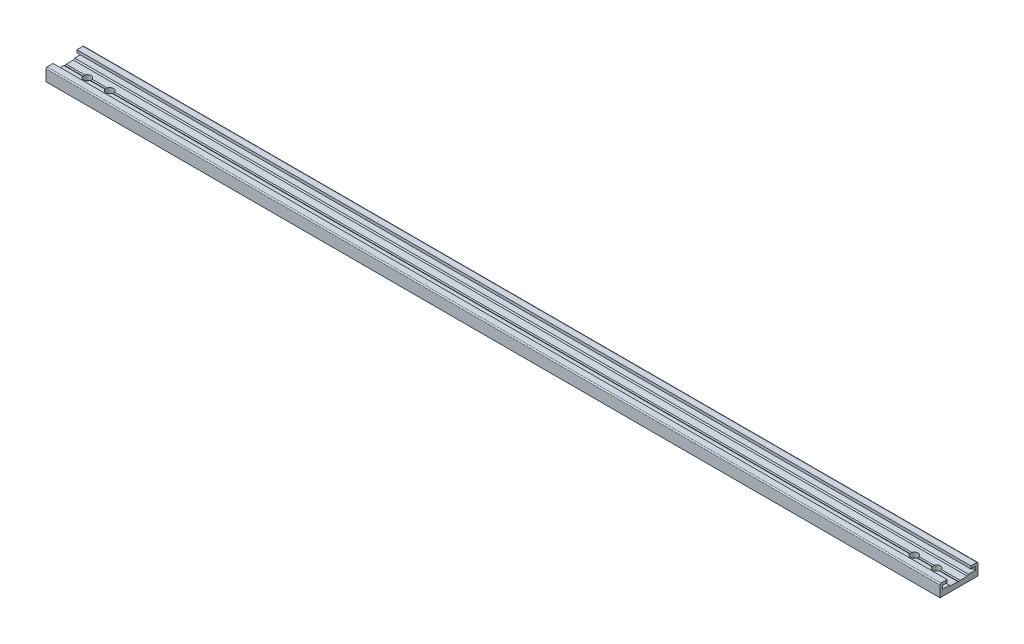
SolidWorks part; units mm, degrees
material "6061 Alloy"
ref_plane "Front" through (0, 0, 0) normal (0, 0, 1) x (1, 0, 0)
ref_plane "Top" through (0, 0, 0) normal (0, 1, 0) x (1, 0, 0)
ref_plane "Right" through (0, 0, 0) normal (1, 0, 0) x (0, 0, -1)
sketch "Sketch1" plane through (0, 0, 0) normal (1, 0, 0) x (0, 0, -1)
  line L0 (0, -2.75) -> (0, 2.75) construction
  line L1 (-0.5, -0.45) -> (0, -0.7387) construction
  line L2 (-3.75, -0.45) -> (-0.5, -0.45) construction
  line L3 (-4.25, 0.05) -> (-3.75, -0.45) construction
  line L4 (-7.3, 0.05) -> (-4.25, 0.05) construction
  line L5 (-7.3, 1.55) -> (-7.3, 0.05) construction
  line L6 (-5.3, 1.55) -> (-7.3, 1.55) construction
  line L7 (-5.3, 2.75) -> (-5.3, 1.55) construction
  line L8 (-8, 2.75) -> (-5.3, 2.75) construction
  line L9 (-8.5, -2.75) -> (-8.5, 2.25) construction
  line L39 (-8.5, -2.75) -> (8.5, -2.75) construction
  line L40 (8.5, -2.75) -> (8.5, 2.25) construction
  line L41 (8, 2.75) -> (5.3, 2.75) construction
  line L42 (5.3, 2.75) -> (5.3, 1.55) construction
  line L43 (5.3, 1.55) -> (7.3, 1.55) construction
  line L44 (7.3, 1.55) -> (7.3, 0.05) construction
  line L45 (7.3, 0.05) -> (4.25, 0.05) construction
  line L46 (4.25, 0.05) -> (3.75, -0.45) construction
  line L47 (3.75, -0.45) -> (0.5, -0.45) construction
  line L48 (0.5, -0.45) -> (0, -0.7387) construction
  arc A0 (8, 2.75) -> (8.5, 2.25) centre (8, 2.25) cw construction
  arc A1 (-8, 2.75) -> (-8.5, 2.25) centre (-8, 2.25) ccw construction
  point P1 (7.3, 0.8)
  point P26 (0, 0)
  point P32 (0, -1.75)
  dimension "D12" = 0.5
  dimension "D1" = 30
  dimension "D3" = 2.3
  dimension "Rail Height" = 5.5
  dimension "D4" = 2.0113
  dimension "D5" = 2.8
  dimension "D7" = 1.2
  dimension "D8" = 3.2
  dimension "D9" = 1.2
  dimension "D10" = 45
  dimension "D11" = 3.75
  dimension "Rail Width" = 17
  dimension "Mounting Hole Depth" = 1
sketch "Sketch2" plane through (0, 0, 0) normal (0, 0, 1) x (1, 0, 0)
  line L0 (1000, 0) -> (-1000, 0) construction
  point P0 (-960, 0)
  point P3 (-900, 0)
  point P4 (0, 0)
  point P6 (-884, 0)
  point P7 (988, 0)
  dimension "Rail Length" = 2000
  dimension "Mounting Hole Ctr to End" = 40
  dimension "Mounting Hole Ctr to Ctr" = 60
  dimension "D2" = 12
  dimension "D1" = 16
sketch "Sketch5" plane through (0, 0, 0) normal (1, 0, 0) x (0, 0, -1)
  line L0 (-8.5, -2.75) -> (8.5, -2.75) construction
  line L1 (8.5, -2.75) -> (8.5, 2.25) construction
  line L2 (8, 2.75) -> (5.3, 2.75) construction
  line L3 (5.3, 2.75) -> (5.3, 1.55) construction
  line L4 (5.3, 1.55) -> (7.3, 1.55) construction
  line L5 (7.3, 1.55) -> (7.3, 0.05) construction
  line L6 (7.3, 0.05) -> (4.25, 0.05) construction
  line L7 (4.25, 0.05) -> (3.75, -0.45) construction
  line L8 (3.75, -0.45) -> (0.5, -0.45) construction
  line L9 (0.5, -0.45) -> (0, -0.7387) construction
  line L10 (-0.5, -0.45) -> (0, -0.7387) construction
  line L11 (-3.75, -0.45) -> (-0.5, -0.45) construction
  line L12 (-4.25, 0.05) -> (-3.75, -0.45) construction
  line L13 (-7.3, 0.05) -> (-4.25, 0.05) construction
  line L14 (-7.3, 1.55) -> (-7.3, 0.05) construction
  line L15 (-5.3, 1.55) -> (-7.3, 1.55) construction
  line L16 (-5.3, 2.75) -> (-5.3, 1.55) construction
  line L17 (-8, 2.75) -> (-5.3, 2.75) construction
  line L18 (-8.5, -2.75) -> (-8.5, 2.25) construction
  line L19 (-8.5, -2.75) -> (8.5, -2.75)
  line L20 (8.5, -2.75) -> (8.5, 2.25)
  line L21 (8, 2.75) -> (5.3, 2.75)
  line L22 (5.3, 2.75) -> (5.3, 1.55)
  line L23 (5.3, 1.55) -> (7.3, 1.55)
  line L24 (7.3, 1.55) -> (7.3, 0.05)
  line L25 (7.3, 0.05) -> (4.25, 0.05)
  line L26 (4.25, 0.05) -> (3.75, -0.45)
  line L27 (3.75, -0.45) -> (0.5, -0.45)
  line L28 (0.5, -0.45) -> (0, -0.7387)
  line L29 (-0.5, -0.45) -> (0, -0.7387)
  line L30 (-3.75, -0.45) -> (-0.5, -0.45)
  line L31 (-4.25, 0.05) -> (-3.75, -0.45)
  line L32 (-7.3, 0.05) -> (-4.25, 0.05)
  line L33 (-7.3, 1.55) -> (-7.3, 0.05)
  line L34 (-5.3, 1.55) -> (-7.3, 1.55)
  line L35 (-5.3, 2.75) -> (-5.3, 1.55)
  line L36 (-8, 2.75) -> (-5.3, 2.75)
  line L37 (-8.5, -2.75) -> (-8.5, 2.25)
  arc A0 (8.5, 2.25) -> (8, 2.75) centre (8, 2.25) ccw construction
  arc A1 (-8, 2.75) -> (-8.5, 2.25) centre (-8, 2.25) ccw construction
  arc A2 (8.5, 2.25) -> (8, 2.75) centre (8, 2.25) ccw
  arc A3 (-8, 2.75) -> (-8.5, 2.25) centre (-8, 2.25) ccw
extrude "Boss-Extrude1" add sketch "Sketch5" along normal blind 400
sketch "Sketch3" plane through (0, 0, 0) normal (0, 0, 1) x (1, 0, 0)
  line L0 (-963.25, -0.45) -> (-963.25, -1.75)
  line L1 (-963.25, -1.75) -> (-961.75, -1.75)
  line L2 (-961.75, -1.75) -> (-961.75, -2.75)
  line L3 (-961.75, -2.75) -> (-960, -2.75)
  line L4 (-960, -2.75) -> (-960, -0.45)
  line L5 (-960, -0.45) -> (-963.25, -0.45)
  line L8 (-963.25, -0.45) -> (-956.75, -0.45) construction
  line L10 (-958.25, -2.75) -> (-961.75, -2.75) construction
  line L19 (400, -2.75) -> (0, -2.75) construction
  dimension "D1" = 1.3
  dimension "D2" = 6.5
  dimension "D3" = 3.5
revolve "Cut-Revolve1" [suppressed] cut sketch "Sketch3" angle 360 mid plane about L4
pattern_linear "LPattern1" [suppressed]
hole_wizard "M3 Clearance Hole1" positions "Sketch6" profile "Sketch7" hole size "M3" standard "ANSI Metric" end condition through all
sketch "Sketch6" plane through (0, -2.75, 0) normal (0, -1, 0) x (-1, 0, 0)
  line L0 (0, 0) -> (-10, 0) construction
  line L1 (-10, 0) -> (-20, 0) construction
  line L3 (-400, 0) -> (-390, 0) construction
  line L4 (-400, -8.5) -> (-400, 8.5) construction
  line L5 (-390, 0) -> (-380, 0) construction
  point P0 (-390, 0)
  point P2 (-380, 0)
  point P4 (-10, 0)
  point P6 (-20, 0)
  dimension "D1" = 10
  dimension "D2" = 10
sketch "Sketch7" plane through (390, -2.75, 0) normal (1, 0, 0) x (0, 0, -1)
  line L0 (0, 0) -> (0, 5.5)
  line L1 (0, 5.5) -> (1.7, 5.5)
  line L2 (1.7, 5.5) -> (1.7, 0)
  line L5 (1.7, 0) -> (0, 0)
  line L11 (0, -6.35) -> (0, 107.95) construction
  dimension "Thru Hole Dia." = 3.4
  dimension "Thru Hole Depth" = 5.5
equation "\"D3@LPattern1\"=\"Mounting Hole Ctr to Ctr@Sketch2\""
equation "\"D2@Sketch2\"=\"Mounting Hole Ctr to End@Sketch2\"*.3"
equation "\"D1@Sketch2\"=\"Mounting Hole Ctr to End@Sketch2\"*.4"
